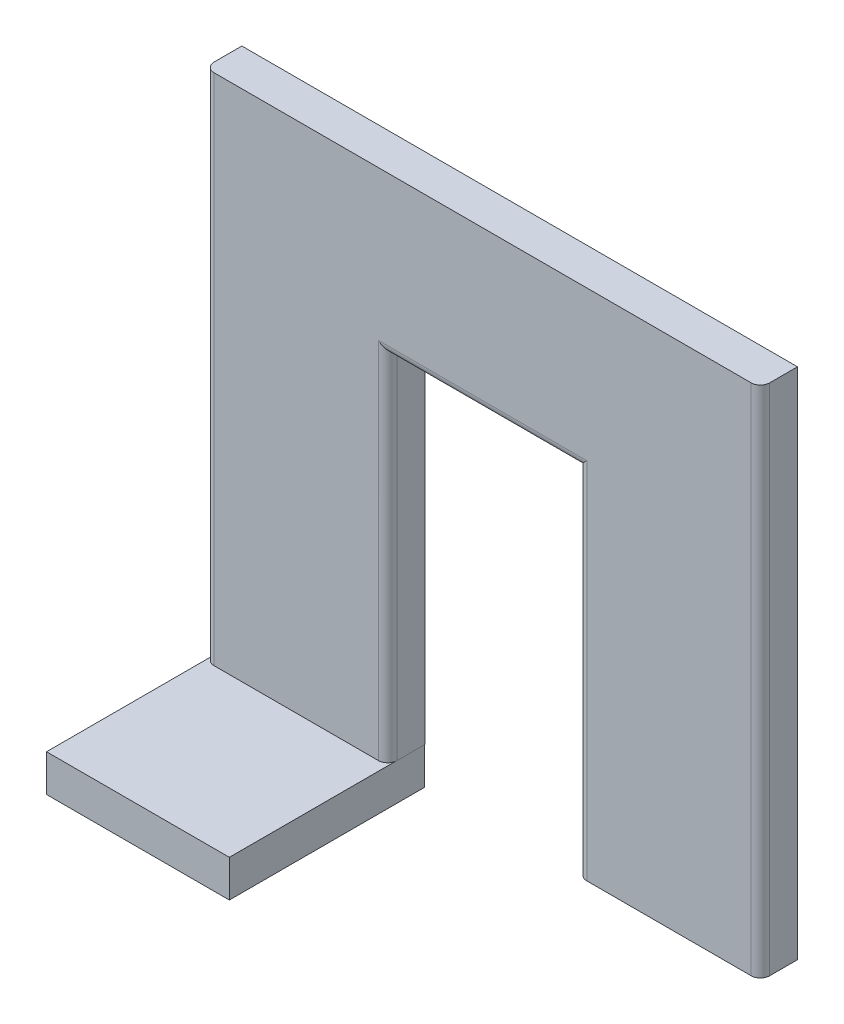
SolidWorks part; units mm, degrees
ref_plane "Front Plane" through (0, 0, 0) normal (0, 0, 1) x (1, 0, 0)
ref_plane "Top Plane" through (0, 0, 0) normal (0, 1, 0) x (1, 0, 0)
ref_plane "Right Plane" through (0, 0, 0) normal (1, 0, 0) x (0, 0, -1)
sketch "Sketch1" plane through (0, 0, 0) normal (0, 0, 1) x (1, 0, 0)
  line L1 (-15, -13.8636) -> (15, -13.8636)
  line L2 (-15, -13.8636) -> (-15, 13.8636)
  line L3 (-15, 13.8636) -> (15, 13.8636)
  line L4 (15, -13.8636) -> (15, 13.8636)
  line L5 (-15, -13.8636) -> (15, 13.8636) construction
  line L6 (-15, 13.8636) -> (15, -13.8636) construction
  point P0 (0, 0)
  dimension "D1" = 30
extrude "Boss-Extrude1" add sketch "Sketch1" along normal blind 2
sketch "Sketch2" plane through (0, 0, 2) normal (0, 0, 1) x (1, 0, 0)
  line L1 (5.1244, -13.8723) -> (-5.1244, -13.8723)
  line L2 (5.1244, -13.8723) -> (5.1244, 5.2837)
  line L3 (5.1244, 5.2837) -> (-5.1244, 5.2837)
  line L4 (-5.1244, -13.8723) -> (-5.1244, 5.2837)
  point P0 (0, 0)
  point P5 (0, 5.2837)
extrude "Cut-Extrude1" cut sketch "Sketch2" against normal blind 2
fillet "Fillet1" radius 0.5 1 edges at (-15, 0, 2)
fillet "Fillet2" radius 0.5 1 edges at (15, 0, 2)
fillet "Fillet3" radius 0.5 1 edges at (-5.1244, -4.2899, 2)
fillet "Fillet4" radius 0.5 1 edges at (5.1244, -4.2899, 2)
fillet "Fillet5" radius 0.5 1 edges at (0, 5.2837, 2)
sketch "Sketch3" plane through (0, -13.8636, 0) normal (0, -1, 0) x (-1, 0, 0)
  line L1 (15, 0) -> (5.129, 0)
  line L2 (15, 0) -> (15, -10.5465)
  line L3 (15, -10.5465) -> (5.129, -10.5465)
  line L4 (5.129, 0) -> (5.129, -10.5465)
  line L5 (15, 0) -> (5.129, -10.5465) construction
  line L6 (15, -10.5465) -> (5.129, 0) construction
  point P4 (10.0645, -5.2733)
extrude "Boss-Extrude2" add sketch "Sketch3" along normal blind 2
